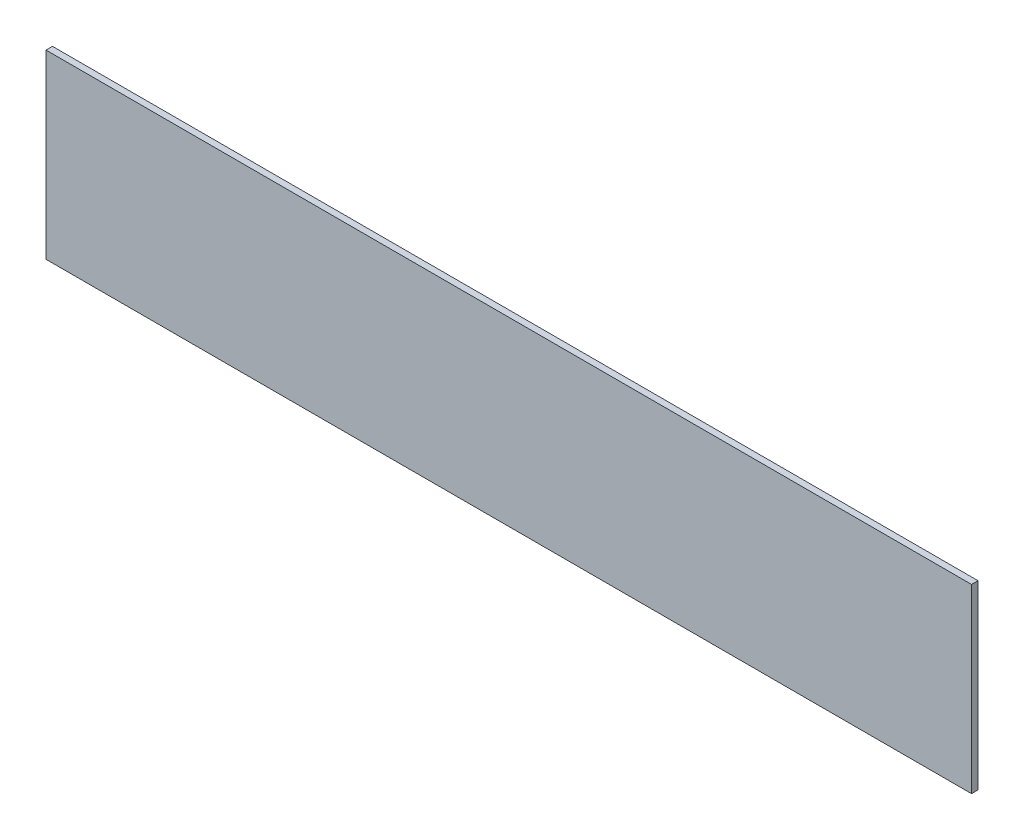
SolidWorks part; units mm, degrees
material "Acrylic (Medium-high impact)"
ref_plane "Front Plane" through (0, 0, 0) normal (0, 0, 1) x (1, 0, 0)
ref_plane "Top Plane" through (0, 0, 0) normal (0, 1, 0) x (1, 0, 0)
ref_plane "Right Plane" through (0, 0, 0) normal (1, 0, 0) x (0, 0, -1)
sketch "Sketch1" plane through (0, 0, 0) normal (0, 0, 1) x (1, 0, 0)
  line L1 (-227.0125, -44.45) -> (227.0125, -44.45)
  line L2 (-227.0125, -44.45) -> (-227.0125, 44.45)
  line L3 (-227.0125, 44.45) -> (227.0125, 44.45)
  line L4 (227.0125, -44.45) -> (227.0125, 44.45)
  line L5 (-227.0125, -44.45) -> (227.0125, 44.45) construction
  line L6 (-227.0125, 44.45) -> (227.0125, -44.45) construction
  point P0 (0, 0)
  dimension "D1" = 88.9
  dimension "D2" = 454.025
extrude "Boss-Extrude1" add sketch "Sketch1" along normal mid plane 3.175
